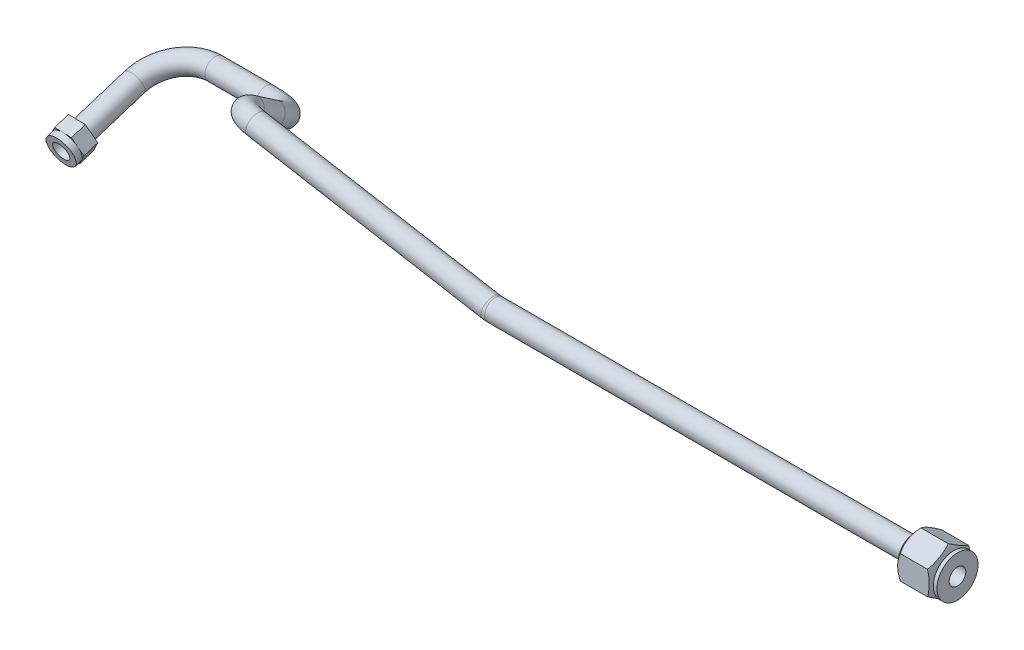
SolidWorks part; units mm, degrees
material "Berilyum Bakır, UNS C17000"
ref_plane "Front" through (0, 0, 0) normal (0, 0, 1) x (1, 0, 0)
ref_plane "Top" through (0, 0, 0) normal (0, 1, 0) x (1, 0, 0)
ref_plane "Right" through (0, 0, 0) normal (1, 0, 0) x (0, 0, -1)
sketch "Sketch1" plane through (0, 0, 0) normal (0, 0, 1) x (1, 0, 0)
  line L0 (-179.5992, 37.1407) -> (-179.627, 0)
  line L1 (169.9273, 39.7777) -> (169.9273, 32.6503)
  line L2 (191.1468, 32.6503) -> (191.1468, 42.5534)
  line L3 (-32.5797, 32.6503) -> (191.1468, 32.6503)
  line L4 (189.3754, 42.5534) -> (191.1468, 42.5534)
  line L5 (189.3754, 42.5534) -> (189.3754, 31.5749)
  line L6 (187.4296, 39.7777) -> (189.3754, 39.7777)
  line L7 (173.5305, 44.141) -> (186.6303, 44.141)
  line L8 (173.5305, 44.141) -> (169.9273, 39.7777)
  line L9 (180.0804, 44.141) -> (180.0804, 32.6503) construction
  line L10 (173.5305, 38.1629) -> (186.6303, 38.1629)
  line L385 (102.2448, 37.3536) -> (-27.8068, 37.6673)
  line L386 (-31.611, 27.7611) -> (102.2472, 27.6357)
  line L392 (-217.6154, -10.0238) -> (-179.627, 0)
  line L561 (-32.5797, 32.6503) -> (-157.7489, 54.6357)
  line L562 (-35.3296, 38.0309) -> (-155.7041, 59.2256)
  line L563 (-124.744, 43.5941) -> (-36.8629, 28.4704)
  line L567 (-158.5061, 49.7008) -> (-124.744, 43.5941)
  line L572 (-184.8659, 36.8413) -> (-184.8801, 16.1522)
  line L573 (-174.9165, 13.6353) -> (-174.8778, 36.2777)
  line L758 (117.2917, 27.4597) -> (169.9572, 27.3938)
  line L759 (117.2605, 37.2544) -> (169.901, 37.2512)
  arc A0 (173.5305, 38.1629) -> (173.5305, 44.141) centre (177.5387, 41.152) cw
  arc A1 (172.4253, 32.6503) -> (173.5305, 38.1629) centre (188.4215, 32.3102) cw
  arc A212 (-157.7489, 54.6357) -> (-179.5992, 37.1407) centre (-159.9064, 34.9378) ccw
  arc A213 (-155.7041, 59.2256) -> (-184.8659, 36.8413) centre (-160.2001, 34.895) ccw
  arc A214 (-158.5061, 49.7008) -> (-174.8778, 36.2777) centre (-160.0145, 34.845) ccw
  arc A236 (-35.3296, 38.0309) -> (-27.8068, 37.6673) centre (-30.3274, 63.5244) ccw
  arc A237 (-36.8629, 28.4704) -> (-31.611, 27.7611) centre (-31.2746, 50.048) ccw
  arc A288 (187.7356, 32.6503) -> (186.6303, 38.1629) centre (171.7393, 32.3102) ccw
  arc A289 (186.6303, 38.1629) -> (186.6303, 44.141) centre (182.6221, 41.152) ccw
  dimension "D1" = 5
revolve "Revolve1" add sketch "Sketch1" angle 360 about L3
sketch "Sketch2" plane through (169.9273, 0, 0) normal (-1, 0, 0) x (0, 0, 1)
  line L1 (0, 44.141) -> (-9.9512, 38.3957)
  line L2 (-9.9512, 38.3957) -> (-9.9512, 26.905)
  line L3 (-9.9512, 26.905) -> (0, 21.1596)
  line L4 (0, 21.1596) -> (9.9512, 26.905)
  line L5 (9.9512, 26.905) -> (9.9512, 38.3957)
  line L6 (9.9512, 38.3957) -> (0, 44.141)
  circle A0 centre (0, 32.6503) radius 9.9512 construction
  circle A1 centre (0, 32.6503) radius 14.4912
extrude "Cut-Extrude1" cut sketch "Sketch2" against normal through all
sketch "Sketch3" plane through (169.9273, 0, 0) normal (-1, 0, 0) x (0, 0, 1)
  circle A0 centre (0, 32.6503) radius 5
  circle A1 centre (0, 32.6503) radius 4 construction
  dimension "D1" = 10
  dimension "D2" = 1
sketch3d "3DSketch1"
  line L0 (-157.7489, 48.3879, -9.0932) -> (-157.7489, 41.4836, -19.1418)
  line L3 (-177.7489, 30.1577, -35.6259) -> (-202.211, 30.1577, -35.6259)
  line L4 (-222.2109, 24.0065, -16.6721) -> (-222.346, 12.5942, 18.4928)
  line L8 (-32.5797, 32.6503, 0) -> (191.1468, 32.6503, 0) construction
  line L9 (-32.5797, 32.6503, 0) -> (-157.7489, 54.6357, 0) construction
  line L29 (-31.7081, 32.6503, 0) -> (169.9273, 32.6503, 0)
  line L30 (-33.4381, 32.8011, 0) -> (-146.8825, 52.7271, 0)
  arc A0 (-202.211, 30.1577, -35.6259) -> (-222.2109, 24.0065, -16.6721) centre (-202.211, 23.9839, -16.6026) ccw
  arc A1 (-157.7489, 41.4836, -19.1418) -> (-177.7489, 30.1577, -35.6259) centre (-177.7489, 41.4836, -19.1418) ccw
  arc A2 (-146.8825, 52.7271, 0) -> (-157.7489, 48.3879, -9.0932) centre (-147.852, 47.207, -8.2819) ccw
  arc A10 (-31.7081, 32.6503, 0) -> (-33.4381, 32.8011, 0) centre (-31.7081, 42.6503, 0) ccw
  point P2 (-179.627, 0, 0)
  point P3 (-222.1381, 30.1577, -35.6259)
  point P7 (-32.5797, 32.6503, 0)
  point P10 (-31.7081, 42.6503, -10)
  point P11 (-202.211, 43.0072, -10.4288)
  point P15 (-157.7489, 30.1577, -35.6259)
  point P18 (-177.7489, 57.9676, -30.4678)
  point P23 (-157.7489, 54.6357, 0)
  point P25 (-149.2848, 39.05, -2.6773)
  dimension "D1" = 20
  dimension "D2" = 10
  dimension "D3" = 20
  dimension "D4" = 10
sweep "Sweep3" add profiles "Sketch3" path "3DSketch1"
sketch "Sketch4" plane through (-0.0531, -4.4804, 13.8057) normal (-0.0037, -0.3087, 0.9512) x (1, -0.0011, 0.0035)
  line L1 (-226.1404, 24.797) -> (-230.3742, 17.9117)
  line L2 (-230.3742, 17.9117) -> (-226.5283, 10.8023)
  line L3 (-226.5283, 10.8023) -> (-218.4485, 10.5783)
  line L4 (-218.4485, 10.5783) -> (-214.2146, 17.4636)
  line L5 (-214.2146, 17.4636) -> (-218.0606, 24.573)
  line L6 (-218.0606, 24.573) -> (-226.1404, 24.797)
  circle A0 centre (-222.2944, 17.6877) radius 7 construction
  dimension "D1" = 14
extrude "Extrude1" add sketch "Sketch4" against normal blind 10
sketch "Sketch5" plane through (-0.0531, -4.4804, 13.8057) normal (-0.0037, -0.3087, 0.9512) x (1, -0.0011, 0.0035)
  circle A0 centre (-222.2944, 17.6877) radius 7
  circle A1 centre (-222.2944, 17.6877) radius 9.9016
extrude "Cut-Extrude2" cut sketch "Sketch5" against normal blind 3
sketch "Çizim2" plane through (191.1468, 0, 0) normal (1, 0, 0) x (0, 0, -1)
  circle A0 centre (0, 32.6503) radius 4
extrude "Kes-Ekstrüzyon1" cut sketch "Çizim2" against normal blind 220
sketch "Çizim3" plane through (-0.0531, -4.4804, 13.8057) normal (-0.0037, -0.3087, 0.9512) x (1, -0.0011, 0.0035)
  circle A0 centre (-222.2944, 17.6877) radius 4
extrude "Kes-Ekstrüzyon2" cut sketch "Çizim3" against normal blind 40
